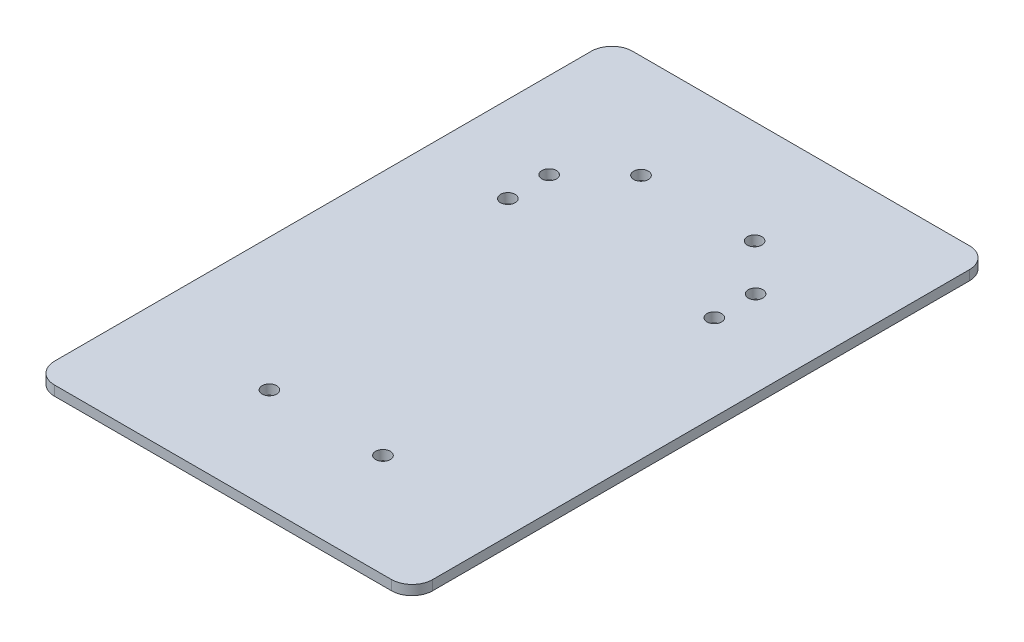
SolidWorks part; units mm, degrees
ref_plane "Front Plane" through (0, 0, 0) normal (0, 0, 1) x (1, 0, 0)
ref_plane "Top Plane" through (0, 0, 0) normal (0, 1, 0) x (1, 0, 0)
ref_plane "Right Plane" through (0, 0, 0) normal (1, 0, 0) x (0, 0, -1)
sketch "Sketch1" plane through (0, 0, 0) normal (0, 1, 0) x (1, 0, 0)
  line L0 (0, 0) -> (0, -177.8)
  line L1 (0, -177.8) -> (116.332, -177.8)
  line L2 (116.332, -177.8) -> (116.332, 0)
  line L3 (0, 0) -> (116.332, 0)
  line L5 (0, 0) -> (25.4, 0)
  line L6 (0, 0) -> (0, -70.104)
  line L7 (0, -70.104) -> (25.4, -70.104)
  line L8 (25.4, 0) -> (25.4, -70.104)
  line L9 (116.332, 0) -> (90.932, 0)
  line L10 (116.332, 0) -> (116.332, -70.104)
  line L11 (116.332, -70.104) -> (90.932, -70.104)
  line L12 (90.932, 0) -> (90.932, -70.104)
  line L13 (0, -177.8) -> (25.4, -177.8)
  line L14 (0, -177.8) -> (0, -107.696)
  line L15 (0, -107.696) -> (25.4, -107.696)
  line L16 (25.4, -177.8) -> (25.4, -107.696)
  line L17 (116.332, -177.8) -> (90.932, -177.8)
  line L18 (116.332, -177.8) -> (116.332, -107.696)
  line L19 (116.332, -107.696) -> (90.932, -107.696)
  line L20 (90.932, -177.8) -> (90.932, -107.696)
  line L21 (35.941, 0) -> (80.391, 0)
  line L22 (35.941, 0) -> (35.941, -44.45)
  line L23 (35.941, -44.45) -> (80.391, -44.45)
  line L24 (80.391, 0) -> (80.391, -44.45)
  point P21 (58.166, -44.45)
  point P22 (58.166, -177.8)
  dimension "D1" = 177.8
  dimension "D2" = 116.332
  dimension "D3" = 70.104
  dimension "D4" = 25.4
  dimension "D5" = 25.4
  dimension "D6" = 70.104
  dimension "D7" = 25.4
  dimension "D8" = 25.4
  dimension "D9" = 44.45
extrude "Boss-Extrude1" add sketch "Sketch1" along normal blind 3 contours L3 L24 L23 L22 L8 L7 L0 L15 L16 L1 L20 L19 L2 L11 L12 | L8 L3 L0 L7 | L1 L16 L15 L0 | L20 L1 L2 L19 | L3 L12 L11 L2
sketch "Sketch3" plane through (0, 3, 0) normal (0, 1, 0) x (1, 0, 0)
  line L0 (0, 0) -> (0, -177.8) construction
  line L1 (0, 0) -> (116.332, 0) construction
  line L2 (116.332, -177.8) -> (116.332, 0) construction
  circle A0 centre (34.544, -11.43) radius 2.25 construction
  circle A1 centre (44.958, -11.43) radius 2.25 construction
  circle A2 centre (26.416, -45.72) radius 2.25
  circle A3 centre (26.416, -58.42) radius 2.25
  circle A4 centre (26.416, -146.304) radius 2.25 construction
  circle A5 centre (26.416, -159.004) radius 2.25 construction
  circle A6 centre (89.916, -45.72) radius 2.25
  circle A7 centre (89.916, -58.42) radius 2.25
  circle A8 centre (89.916, -146.304) radius 2.25 construction
  circle A9 centre (89.916, -159.004) radius 2.25 construction
  dimension "D1" = 4.5
  dimension "D2" = 4.5
  dimension "D3" = 4.5
  dimension "D4" = 4.5
  dimension "D5" = 4.5
  dimension "D6" = 4.5
  dimension "D7" = 4.5
  dimension "D8" = 4.5
  dimension "D9" = 4.5
  dimension "D10" = 4.5
  dimension "D11" = 34.544
  dimension "D12" = 44.958
  dimension "D13" = 11.43
  dimension "D14" = 26.416
  dimension "D15" = 26.416
  dimension "D16" = 45.72
  dimension "D17" = 58.42
  dimension "D18" = 146.304
  dimension "D19" = 159.004
extrude "Cut-Extrude1" cut sketch "Sketch3" against normal through all both and the other way through all
sketch "Sketch4" plane through (0, 3, 0) normal (0, 1, 0) x (1, 0, 0)
  line L0 (40.7035, -146.05) -> (75.6285, -146.05) construction
  line L1 (40.7035, -31.75) -> (75.6285, -31.75) construction
  line L2 (0, 0) -> (116.332, 0) construction
  line L3 (0, -177.8) -> (116.332, -177.8) construction
  circle A0 centre (40.7035, -31.75) radius 2.25
  circle A1 centre (75.6285, -31.75) radius 2.25
  circle A2 centre (40.7035, -146.05) radius 2.25
  circle A3 centre (75.6285, -146.05) radius 2.25
  point P8 (58.166, 0)
  point P9 (58.166, -31.75)
  point P12 (58.166, -146.05)
  dimension "D1" = 4.5
  dimension "D2" = 4.5
  dimension "D3" = 4.5
  dimension "D4" = 4.5
  dimension "D5" = 34.925
  dimension "D6" = 34.925
  dimension "D7" = 31.75
  dimension "D8" = 31.75
extrude "Cut-Extrude2" cut sketch "Sketch4" against normal through all both
fillet "Fillet1" radius 6.35 4 edges at (0, 1.5, 177.8) (116.332, 1.5, 177.8) (116.332, 1.5, 0) (0, 1.5, 0)
